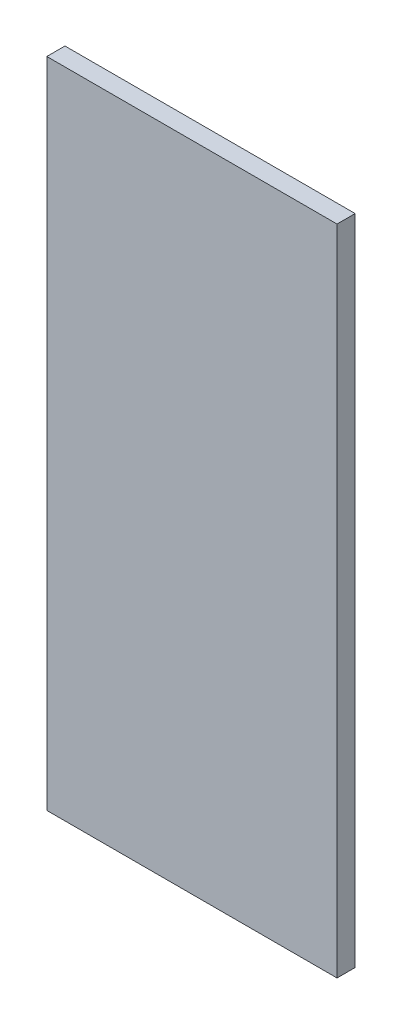
SolidWorks part; units mm, degrees
ref_plane "Front Plane" through (0, 0, 0) normal (0, 0, 1) x (1, 0, 0)
ref_plane "Top Plane" through (0, 0, 0) normal (0, 1, 0) x (1, 0, 0)
ref_plane "Right Plane" through (0, 0, 0) normal (1, 0, 0) x (0, 0, -1)
sketch "Sketch1" plane through (0, 0, 0) normal (0, 0, 1) x (1, 0, 0)
  line L1 (0, 0) -> (50.8, 0)
  line L2 (0, 0) -> (0, 114.3)
  line L3 (0, 114.3) -> (50.8, 114.3)
  line L4 (50.8, 0) -> (50.8, 114.3)
  dimension "D1" = 50.8
  dimension "D2" = 114.3
extrude "Boss-Extrude1" add sketch "Sketch1" along normal blind 3.175
